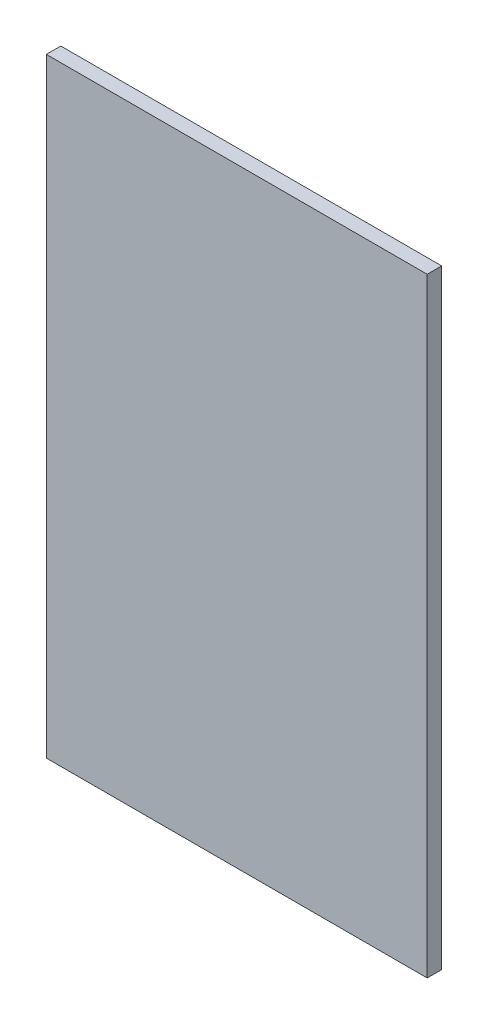
SolidWorks part; units mm, degrees
ref_plane "Plan de face" through (0, 0, 0) normal (0, 0, 1) x (1, 0, 0)
ref_plane "Plan de dessus" through (0, 0, 0) normal (0, 1, 0) x (1, 0, 0)
ref_plane "Plan de droite" through (0, 0, 0) normal (1, 0, 0) x (0, 0, -1)
sketch "Esquisse1" plane through (0, 0, 0) normal (0, 0, 1) x (1, 0, 0)
  line L1 (0, 0) -> (500, 0)
  line L2 (0, 0) -> (0, 800)
  line L3 (0, 800) -> (500, 800)
  line L4 (500, 0) -> (500, 800)
  dimension "D1" = 500
  dimension "D2" = 800
extrude "Boss.-Extru.1" add sketch "Esquisse1" along normal blind 19
